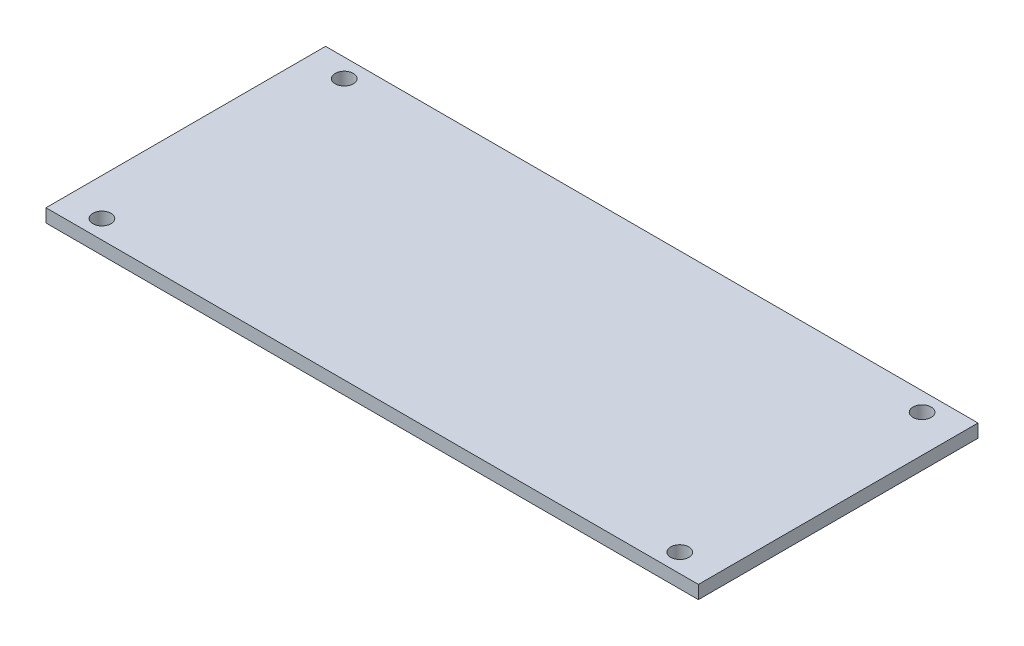
SolidWorks part; units mm, degrees
ref_plane "Front" through (0, 0, 0) normal (0, 0, 1) x (1, 0, 0)
ref_plane "Top" through (0, 0, 0) normal (0, 1, 0) x (1, 0, 0)
ref_plane "Right" through (0, 0, 0) normal (1, 0, 0) x (0, 0, -1)
sketch "Sketch3" plane through (0, 0, 0) normal (0, 1, 0) x (1, 0, 0)
  line L1 (-35, -15) -> (35, -15)
  line L2 (-35, -15) -> (-35, 15)
  line L3 (-35, 15) -> (35, 15)
  line L4 (35, -15) -> (35, 15)
  line L5 (-35, -15) -> (35, 15) construction
  line L6 (-35, 15) -> (35, -15) construction
  line L7 (-31, -13) -> (31, -13) construction
  line L8 (-31, -13) -> (-31, 13) construction
  line L9 (-31, 13) -> (31, 13) construction
  line L10 (31, -13) -> (31, 13) construction
  line L11 (-31, -13) -> (31, 13) construction
  line L12 (-31, 13) -> (31, -13) construction
  circle A0 centre (-31, 13) radius 0.975
  circle A1 centre (31, 13) radius 0.975
  circle A2 centre (31, -13) radius 0.975
  circle A3 centre (-31, -13) radius 0.975
  point P0 (0, 0)
  point P6 (0, 0)
  dimension "D5" = 1.95
  dimension "D1" = 70
  dimension "D2" = 30
  dimension "D3" = 26
  dimension "D4" = 62
extrude "Boss-Extrude1" add sketch "Sketch3" along normal blind 1.42
